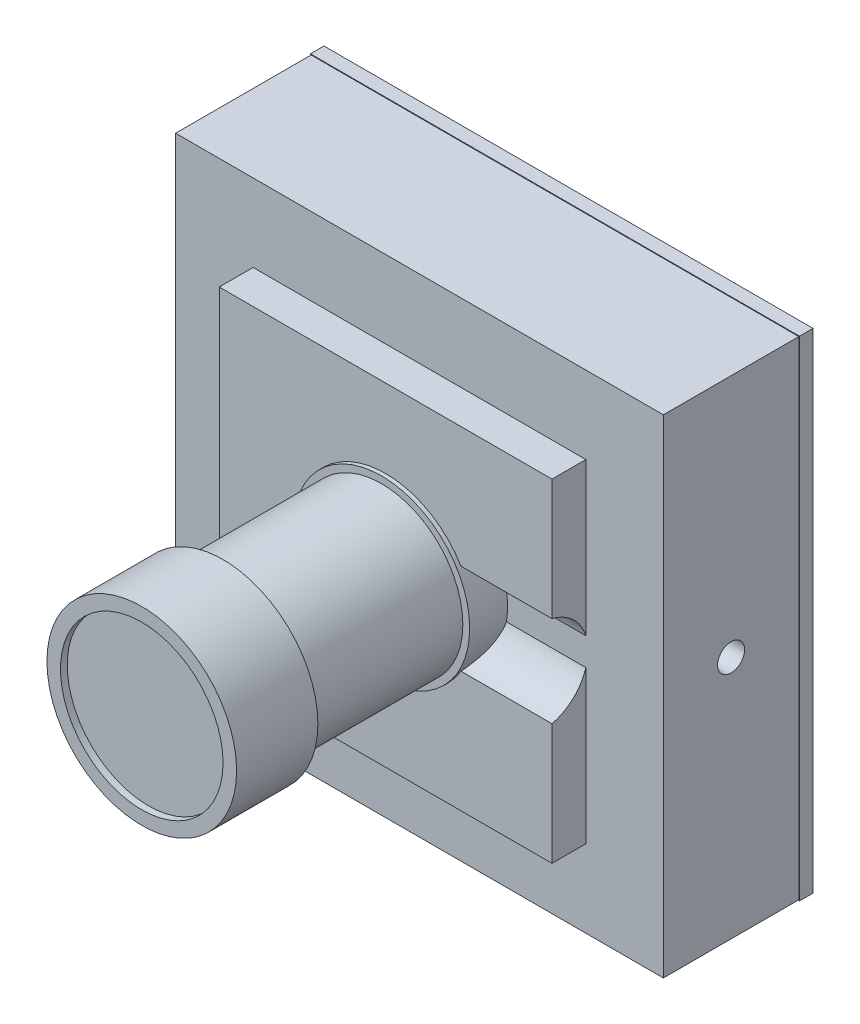
SolidWorks part; units mm, degrees
ref_plane "前视基准面" through (0, 0, 0) normal (0, 0, 1) x (1, 0, 0)
ref_plane "上视基准面" through (0, 0, 0) normal (0, 1, 0) x (1, 0, 0)
ref_plane "右视基准面" through (0, 0, 0) normal (1, 0, 0) x (0, 0, -1)
other "Configuration Table"
sketch "草图1" plane through (0, 0, 0) normal (0, 0, 1) x (1, 0, 0)
  line L1 (-18, -18) -> (18, -18)
  line L2 (-18, -18) -> (-18, 18)
  line L3 (-18, 18) -> (18, 18)
  line L4 (18, -18) -> (18, 18)
  line L5 (-18, -18) -> (18, 18) construction
  line L6 (-18, 18) -> (18, -18) construction
  point P0 (0, 0)
  dimension "D1" = 36
  dimension "D2" = 36
extrude "凸台-拉伸1" add sketch "草图1" along normal blind 10
sketch "草图2" plane through (0, 0, 10) normal (0, 0, 1) x (1, 0, 0)
  line L1 (-12.28, -12.28) -> (12.28, -12.28)
  line L2 (-12.28, -12.28) -> (-12.28, 12.28)
  line L3 (-12.28, 12.28) -> (12.28, 12.28)
  line L4 (12.28, -12.28) -> (12.28, 12.28)
  line L5 (-12.28, -12.28) -> (12.28, 12.28) construction
  line L6 (-12.28, 12.28) -> (12.28, -12.28) construction
  point P0 (0, 0)
  dimension "D1" = 24.56
  dimension "D2" = 24.56
extrude "凸台-拉伸2" add sketch "草图2" along normal blind 2.5
sketch "草图3" plane through (0, 0, 12.5) normal (0, 0, 1) x (1, 0, 0)
  circle A0 centre (0, 0) radius 6
  dimension "D1" = 12
extrude "凸台-拉伸3" add sketch "草图3" along normal blind 12
sketch "草图4" plane through (0, 0, 24.5) normal (0, 0, 1) x (1, 0, 0)
  circle A0 centre (0, 0) radius 7
  dimension "D1" = 14
extrude "凸台-拉伸4" add sketch "草图4" along normal blind 6
sketch "草图5" plane through (0, 0, 30.5) normal (0, 0, 1) x (1, 0, 0)
  circle A0 centre (0, 0) radius 6
  dimension "D1" = 12
extrude "切除-拉伸1" cut sketch "草图5" against normal blind 0.5
sketch "草图7" plane through (0, 0, 12.5) normal (0, 0, 1) x (1, 0, 0)
  circle A0 centre (0, 0) radius 6.5
  dimension "D2" = 13
extrude "凸台-拉伸5" add sketch "草图7" along normal blind 0.3
sketch "草图8" plane through (0, 0, 12.5) normal (0, 0, 1) x (1, 0, 0)
  line L0 (-18, 0) -> (18, 0) construction
  line L1 (18, -18) -> (18, 18) construction
  line L2 (0, -18) -> (0, 18) construction
  line L3 (18, 18) -> (-18, 18) construction
  line L4 (5.566, 3.357) -> (12.28, 3.357)
  line L5 (12.28, -12.28) -> (12.28, 12.28) construction
  line L6 (12.28, 3.357) -> (12.28, -3.357)
  line L7 (5.566, -3.357) -> (12.28, -3.357)
  arc A1 (5.566, -3.357) -> (5.566, 3.357) centre (0, 0) ccw
  circle A3 centre (0, 0) radius 6.5 construction
  point P3 (6.7872, 1.7129)
  point P6 (0, 0)
  point P12 (0, 0)
  point P21 (12.28, 0)
sketch "草图9" plane through (12.28, 0, 0) normal (1, 0, 0) x (0, 0, -1)
  line L0 (-12.5, 0) -> (-10, 0) construction
  line L1 (-12.5, 3.357) -> (-12.5, -3.357) construction
  line L2 (-10, -12.28) -> (-10, 12.28) construction
  line L3 (-10, -1.0202) -> (-10, 1.0202)
  line L7 (-12.5, 3.357) -> (-12.5, -3.357) construction
  line L8 (-12.5, 3.357) -> (-12.5, -3.357)
  arc A0 (-12.8093, -0.7319) -> (-12.8093, 0.7319) centre (-11.5, 0) ccw construction
  arc A2 (-12.5, 3.357) -> (-10, 1.0202) centre (-13.2957, 0) cw
  arc A3 (-10, -1.0202) -> (-12.5, -3.357) centre (-13.2957, 0) cw
  point P10 (0, 0)
  point P12 (0, 0)
  dimension "D1" = 3
  dimension "D2" = 3.45
extrude "切除-拉伸2" cut sketch "草图9" against normal up to surface (6.714 mm away)
sketch "草图10" plane through (18, 0, 0) normal (1, 0, 0) x (0, 0, -1)
  line L0 (0, 0) -> (-10, 0) construction
  line L1 (-10, -18) -> (-10, 18) construction
  line L2 (-5, 18) -> (-5, -18) construction
  line L3 (-10, 18) -> (0, 18) construction
  line L4 (-10, -18) -> (0, -18) construction
  circle A0 centre (-5, 0) radius 1
  dimension "D1" = 2
extrude "切除-拉伸3" cut sketch "草图10" against normal blind 3
mirror "镜向1" about plane through (0, 0, 0) normal (1, 0, 0) of "切除-拉伸3"
sketch "草图11" plane through (0, 0, 0) normal (0, 0, -1) x (-1, 0, 0)
  line L1 (-18.05, -18.05) -> (18.05, -18.05)
  line L2 (-18.05, -18.05) -> (-18.05, 18.05)
  line L3 (-18.05, 18.05) -> (18.05, 18.05)
  line L4 (18.05, -18.05) -> (18.05, 18.05)
  line L5 (-18.05, -18.05) -> (18.05, 18.05) construction
  line L6 (-18.05, 18.05) -> (18.05, -18.05) construction
  point P0 (0, 0)
  dimension "D1" = 36.1
  dimension "D2" = 36.1
extrude "凸台-拉伸6" add sketch "草图11" along normal blind 1
sketch "草图12" plane through (0, 0, -1) normal (0, 0, -1) x (-1, 0, 0)
  line L0 (0, 18.05) -> (0, -18.05) construction
  line L1 (-18.05, -18.05) -> (18.05, -18.05) construction
  line L2 (-5.5, -10.55) -> (5.5, -10.55)
  line L3 (5.5, -10.55) -> (5.5, -15.55)
  line L4 (5.5, -15.55) -> (-5.5, -15.55)
  line L5 (-5.5, -10.55) -> (-5.5, -15.55)
  point P6 (0, 0)
  point P12 (0, -15.55)
  point P13 (0, -10.55)
  dimension "D1" = 2.5
  dimension "D2" = 5
  dimension "D3" = 5.5
extrude "切除-拉伸4" cut sketch "草图12" against normal blind 5
